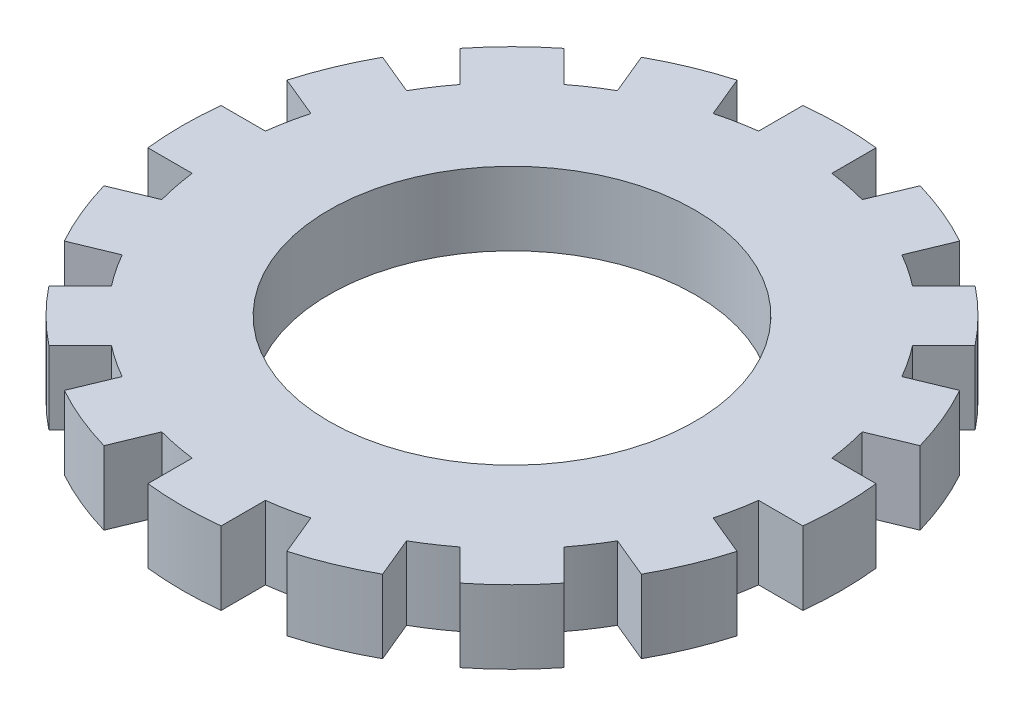
SolidWorks part; units mm, degrees
ref_plane "Front Plane" through (0, 0, 0) normal (0, 0, 1) x (1, 0, 0)
ref_plane "Top Plane" through (0, 0, 0) normal (0, 1, 0) x (1, 0, 0)
ref_plane "Right Plane" through (0, 0, 0) normal (1, 0, 0) x (0, 0, -1)
sketch "Sketch1" plane through (0, 0, 0) normal (0, 1, 0) x (1, 0, 0)
  line L0 (0, 0) -> (25, 0) construction
  line L1 (33.8205, -19.4209) -> (39.4037, -21.7335)
  line L6 (38.6782, 5) -> (44.7214, 5)
  line L8 (38.6782, -5) -> (44.7214, -5)
  line L10 (37.6474, -10.1821) -> (43.2306, -12.4947)
  line L11 (23.8141, -30.8851) -> (28.0872, -35.1583)
  line L12 (30.8851, -23.8141) -> (35.1583, -28.0872)
  line L13 (10.1821, -37.6474) -> (12.4947, -43.2306)
  line L14 (19.4209, -33.8205) -> (21.7335, -39.4037)
  line L15 (-5, -38.6782) -> (-5, -44.7214)
  line L16 (5, -38.6782) -> (5, -44.7214)
  line L17 (-19.4209, -33.8205) -> (-21.7335, -39.4037)
  line L18 (-10.1821, -37.6474) -> (-12.4947, -43.2306)
  line L19 (-30.8851, -23.8141) -> (-35.1583, -28.0872)
  line L20 (-23.8141, -30.8851) -> (-28.0872, -35.1583)
  line L21 (-37.6474, -10.1821) -> (-43.2306, -12.4947)
  line L22 (-33.8205, -19.4209) -> (-39.4037, -21.7335)
  line L23 (-38.6782, 5) -> (-44.7214, 5)
  line L24 (-38.6782, -5) -> (-44.7214, -5)
  line L25 (-33.8205, 19.4209) -> (-39.4037, 21.7335)
  line L26 (-37.6474, 10.1821) -> (-43.2306, 12.4947)
  line L27 (-23.8141, 30.8851) -> (-28.0872, 35.1583)
  line L28 (-30.8851, 23.8141) -> (-35.1583, 28.0872)
  line L29 (-10.1821, 37.6474) -> (-12.4947, 43.2306)
  line L30 (-19.4209, 33.8205) -> (-21.7335, 39.4037)
  line L31 (5, 38.6782) -> (5, 44.7214)
  line L32 (-5, 38.6782) -> (-5, 44.7214)
  line L33 (19.4209, 33.8205) -> (21.7335, 39.4037)
  line L34 (10.1821, 37.6474) -> (12.4947, 43.2306)
  line L35 (30.8851, 23.8141) -> (35.1583, 28.0872)
  line L36 (23.8141, 30.8851) -> (28.0872, 35.1583)
  line L37 (37.6474, 10.1821) -> (43.2306, 12.4947)
  line L38 (33.8205, 19.4209) -> (39.4037, 21.7335)
  circle A0 centre (0, 0) radius 25
  arc A1 (38.6782, 5) -> (38.6782, -5) centre (0, 0) ccw
  arc A2 (44.7214, -5) -> (44.7214, 5) centre (0, 0) ccw
  arc A3 (37.6474, -10.1821) -> (33.8205, -19.4209) centre (0, 0) ccw
  arc A4 (39.4037, -21.7335) -> (43.2306, -12.4947) centre (0, 0) ccw
  arc A5 (30.8851, -23.8141) -> (23.8141, -30.8851) centre (0, 0) ccw
  arc A6 (28.0872, -35.1583) -> (35.1583, -28.0872) centre (0, 0) ccw
  arc A7 (19.4209, -33.8205) -> (10.1821, -37.6474) centre (0, 0) ccw
  arc A8 (12.4947, -43.2306) -> (21.7335, -39.4037) centre (0, 0) ccw
  arc A9 (5, -38.6782) -> (-5, -38.6782) centre (0, 0) ccw
  arc A10 (-5, -44.7214) -> (5, -44.7214) centre (0, 0) ccw
  arc A11 (-10.1821, -37.6474) -> (-19.4209, -33.8205) centre (0, 0) ccw
  arc A12 (-21.7335, -39.4037) -> (-12.4947, -43.2306) centre (0, 0) ccw
  arc A13 (-23.8141, -30.8851) -> (-30.8851, -23.8141) centre (0, 0) ccw
  arc A14 (-35.1583, -28.0872) -> (-28.0872, -35.1583) centre (0, 0) ccw
  arc A15 (-33.8205, -19.4209) -> (-37.6474, -10.1821) centre (0, 0) ccw
  arc A16 (-43.2306, -12.4947) -> (-39.4037, -21.7335) centre (0, 0) ccw
  arc A17 (-38.6782, -5) -> (-38.6782, 5) centre (0, 0) ccw
  arc A18 (-44.7214, 5) -> (-44.7214, -5) centre (0, 0) ccw
  arc A19 (-37.6474, 10.1821) -> (-33.8205, 19.4209) centre (0, 0) ccw
  arc A20 (-39.4037, 21.7335) -> (-43.2306, 12.4947) centre (0, 0) ccw
  arc A21 (-30.8851, 23.8141) -> (-23.8141, 30.8851) centre (0, 0) ccw
  arc A22 (-28.0872, 35.1583) -> (-35.1583, 28.0872) centre (0, 0) ccw
  arc A23 (-19.4209, 33.8205) -> (-10.1821, 37.6474) centre (0, 0) ccw
  arc A24 (-12.4947, 43.2306) -> (-21.7335, 39.4037) centre (0, 0) ccw
  arc A25 (-5, 38.6782) -> (5, 38.6782) centre (0, 0) ccw
  arc A26 (5, 44.7214) -> (-5, 44.7214) centre (0, 0) ccw
  arc A27 (10.1821, 37.6474) -> (19.4209, 33.8205) centre (0, 0) ccw
  arc A28 (21.7335, 39.4037) -> (12.4947, 43.2306) centre (0, 0) ccw
  arc A29 (23.8141, 30.8851) -> (30.8851, 23.8141) centre (0, 0) ccw
  arc A30 (35.1583, 28.0872) -> (28.0872, 35.1583) centre (0, 0) ccw
  arc A31 (33.8205, 19.4209) -> (37.6474, 10.1821) centre (0, 0) ccw
  arc A32 (43.2306, 12.4947) -> (39.4037, 21.7335) centre (0, 0) ccw
  point P70 (0, 0)
  dimension "D1" = 90
  dimension "D2" = 78
  dimension "D3" = 50
  dimension "D4" = 16
extrude "Boss-Extrude2" add sketch "Sketch1" against normal blind 10 contours A1 A3 A0 | L25 A20 L26 A1 | L27 A22 L28 A1 | L29 A24 L30 A1 | L31 A26 L32 A1 | L33 A28 L34 A1 | L37 A32 L38 A1 | A3 L8 A2 L6 | L1 A4 L10 A1 | L11 A6 L12 A1 | L13 A8 L14 A1 | L15 A10 L16 A1 | A18 L24 A17 L23 | L35 A30 L36 A29 | L21 A16 L22 A15 | L19 A14 L20 A13 | L17 A12 L18 A11
sketch "Sketch2" plane through (0, -10, 0) normal (0, -1, 0) x (1, 0, 0)
  circle A0 centre (0, 0) radius 25
extrude "Cut-Extrude1" cut sketch "Sketch2" against normal up to surface (10 mm away) up to face at (0, 0, 0)
